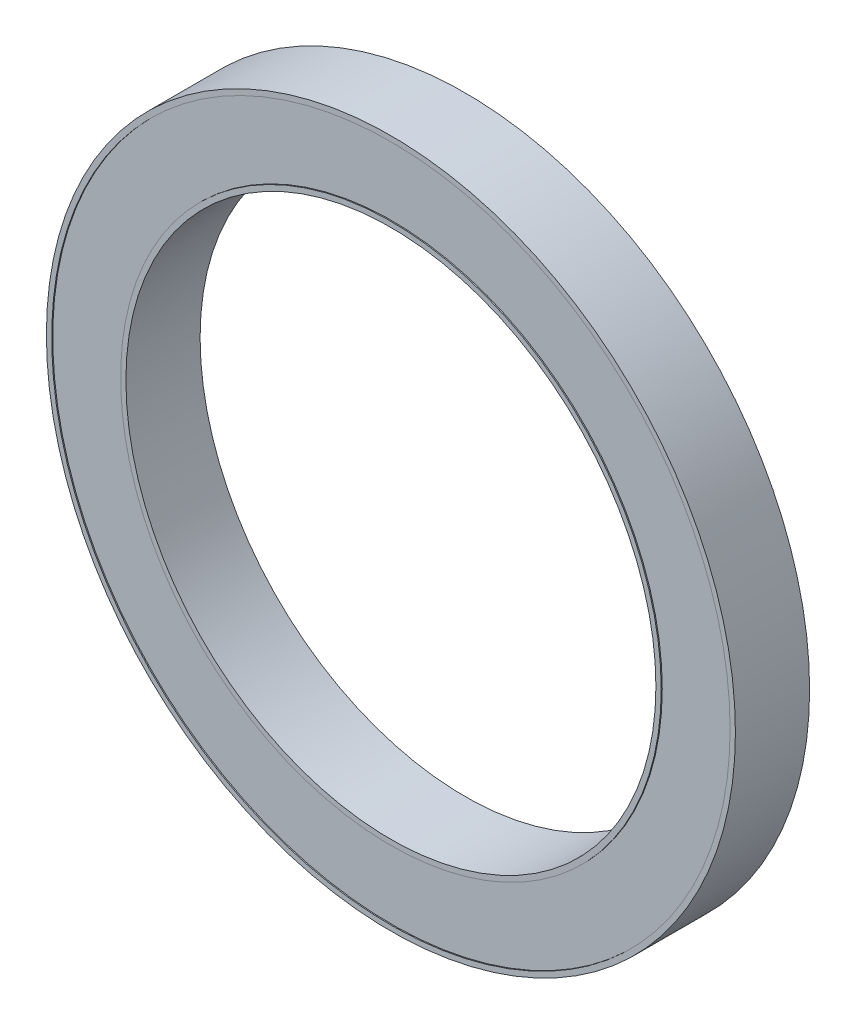
SolidWorks part; units mm, degrees
ref_plane "Front Plane" through (0, 0, 0) normal (0, 0, 1) x (1, 0, 0)
ref_plane "Top Plane" through (0, 0, 0) normal (0, 1, 0) x (1, 0, 0)
ref_plane "Right Plane" through (0, 0, 0) normal (1, 0, 0) x (0, 0, -1)
sketch "Sketch1" plane through (0, 0, 0) normal (0, 0, 1) x (1, 0, 0)
  circle A0 centre (0, 0) radius 32.5
  circle A1 centre (0, 0) radius 25
  dimension "D1" = 65
  dimension "D2" = 50
extrude "Boss-Extrude1" add sketch "Sketch1" along normal blind 7
sketch "Sketch2" plane through (0, 0, 0) normal (0, 0, -1) x (-1, 0, 0)
  circle A0 centre (0, 0) radius 25.5
  circle A1 centre (0, 0) radius 32
  dimension "D1" = 64
  dimension "D2" = 51
extrude "Cut-Extrude1" cut sketch "Sketch2" against normal blind 0.1
sketch "Sketch3" plane through (0, 0, 7) normal (0, 0, 1) x (1, 0, 0)
  circle A1 centre (0, 0) radius 32
  circle A2 centre (0, 0) radius 32
  circle A3 centre (0, 0) radius 25.5
  circle A4 centre (0, 0) radius 25.5
  dimension "D1" = 0
  dimension "D2" = 0
extrude "Cut-Extrude2" cut sketch "Sketch3" against normal blind 0.1
equation "\"I\" = 50mm"
equation "\"E\" = 65mm"
equation "\"T\"= 7mm"
equation "\"D1@Sketch1\"=\"E\""
equation "\"D2@Sketch1\"=\"I\""
equation "\"D1@Sketch2\"=\"E\"-1"
equation "\"D2@Sketch2\"=\"I\"+1"
equation "\"D1@Boss-Extrude1\"=\"T\""
